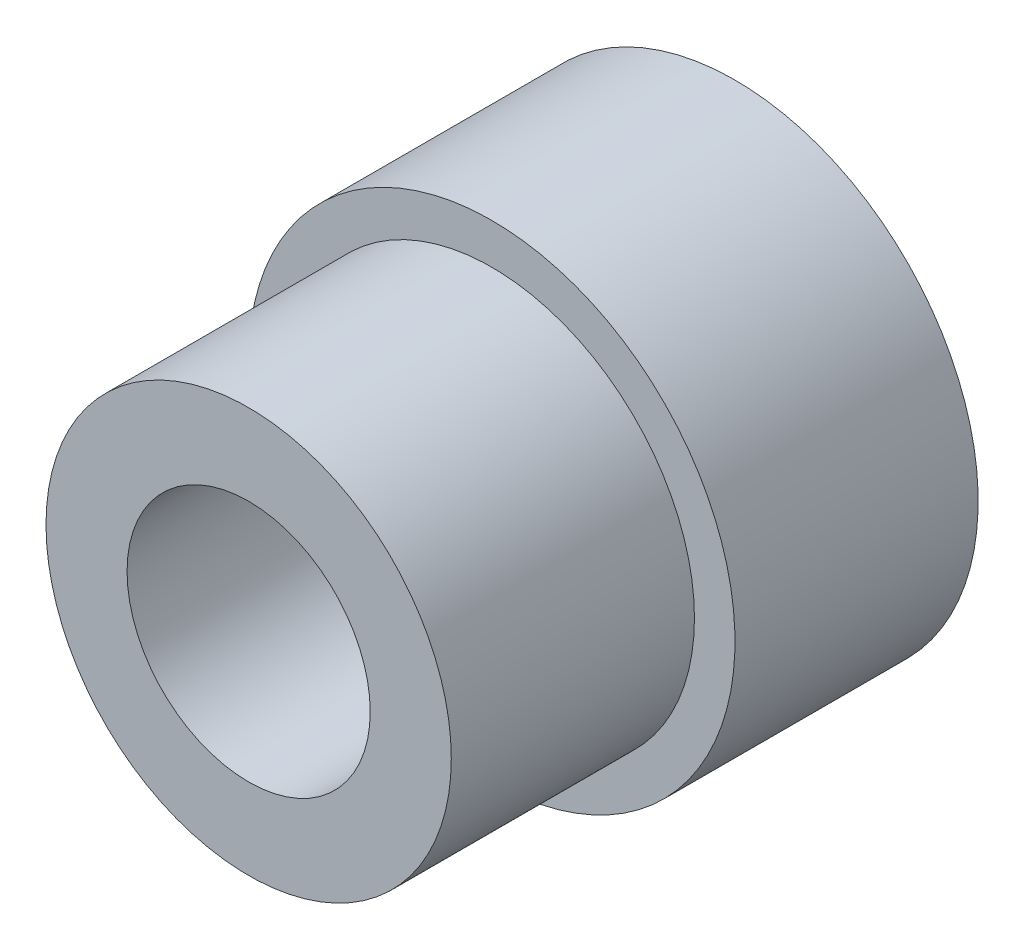
SolidWorks part; units mm, degrees
ref_plane "Front Plane" through (0, 0, 0) normal (0, 0, 1) x (1, 0, 0)
ref_plane "Top Plane" through (0, 0, 0) normal (0, 1, 0) x (1, 0, 0)
ref_plane "Right Plane" through (0, 0, 0) normal (1, 0, 0) x (0, 0, -1)
sketch "Sketch1" plane through (0, 0, 0) normal (0, 0, 1) x (1, 0, 0)
  circle A0 centre (0, 0) radius 25
  circle A1 centre (0, 0) radius 15
  dimension "D1" = 50
  dimension "D2" = 30
extrude "Boss-Extrude1" add sketch "Sketch1" along normal blind 30
sketch "Sketch2" plane through (0, 0, 0) normal (0, 0, -1) x (-1, 0, 0)
  circle A0 centre (0, 0) radius 30
  dimension "D1" = 60
extrude "Boss-Extrude2" add sketch "Sketch2" along normal blind 30
sketch "Sketch3" plane through (0, 0, 0) normal (0, 0, 1) x (1, 0, 0)
  circle A0 centre (0, 0) radius 15
  dimension "D1" = 30
extrude "Cut-Extrude1" cut sketch "Sketch3" against normal blind 30
